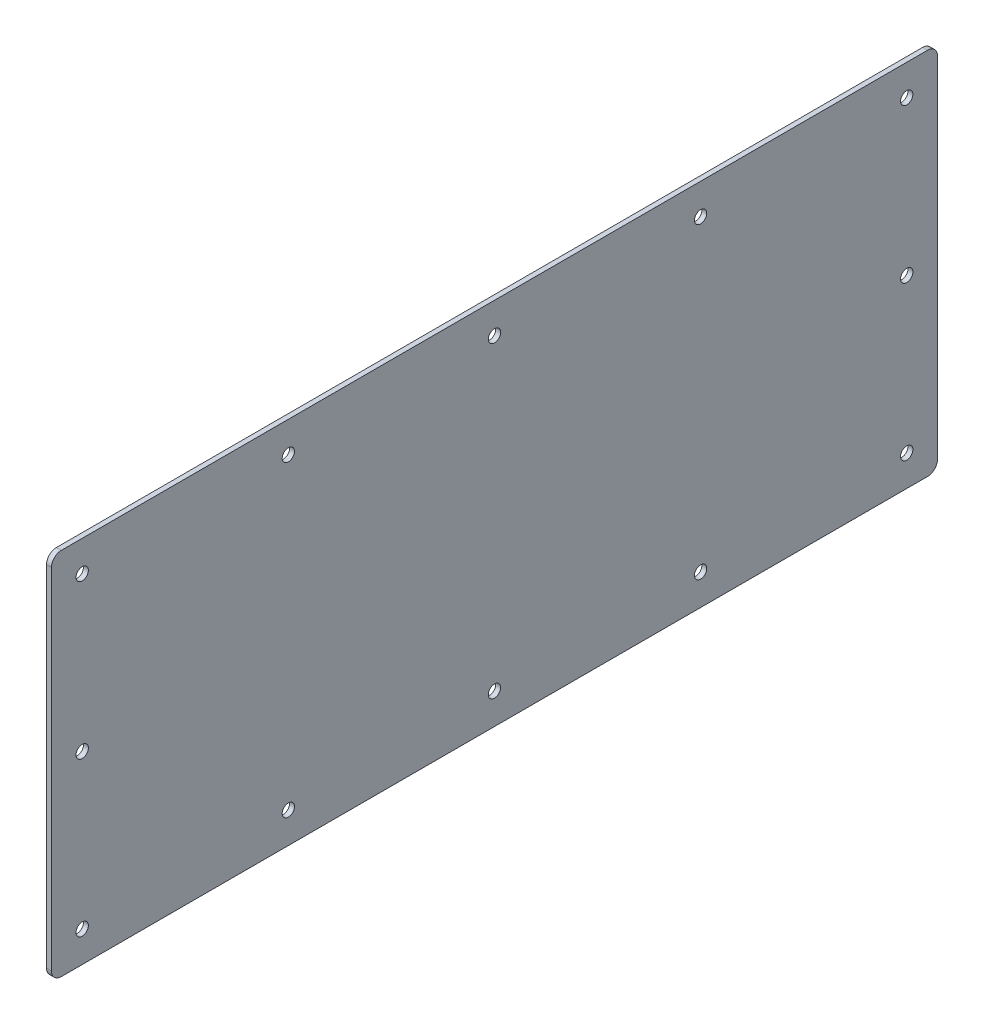
SolidWorks part; units mm, degrees
ref_plane "Front Plane" through (0, 0, 0) normal (1, 0, 0) x (0, 1, 0)
ref_plane "Top Plane" through (0, 0, 0) normal (0, 0, 1) x (0, 1, 0)
ref_plane "Right Plane" through (0, 0, 0) normal (0, 1, 0) x (-1, 0, 0)
sketch "Sketch1" plane through (0, 0, 0) normal (1, 0, 0) x (0, 1, 0)
  line L1 (-95.25, -228.6) -> (95.25, -228.6)
  line L2 (-95.25, -228.6) -> (-95.25, 228.6)
  line L3 (-95.25, 228.6) -> (95.25, 228.6)
  line L4 (95.25, -228.6) -> (95.25, 228.6)
  line L5 (-95.25, -228.6) -> (95.25, 228.6) construction
  line L6 (-95.25, 228.6) -> (95.25, -228.6) construction
  point P0 (0, 0)
  dimension "D1" = 190.5
  dimension "D2" = 457.2
extrude "Boss-Extrude1" add sketch "Sketch1" along normal blind 2.54
fillet "Fillet1" radius 5.08 4 edges at (1.27, 95.25, -228.6) (1.27, -95.25, -228.6) (1.27, -95.25, 228.6) (1.27, 95.25, 228.6)
sketch "Sketch2" plane through (0, 0, 0) normal (-1, 0, 0) x (0, 0, 1)
  circle A1 centre (-257.175, 0) radius 3.175
  circle A2 centre (-257.175, 0) radius 3.175
  circle A3 centre (-106.3625, -79.375) radius 3.175
  circle A4 centre (-106.3625, -79.375) radius 3.175
  circle A5 centre (0, -79.375) radius 3.175
  circle A6 centre (0, -79.375) radius 3.175
  circle A7 centre (106.3625, -79.375) radius 3.175
  circle A8 centre (106.3625, -79.375) radius 3.175
  circle A9 centre (212.725, -79.375) radius 3.175
  circle A10 centre (212.725, -79.375) radius 3.175
  circle A11 centre (212.725, 79.375) radius 3.175
  circle A12 centre (212.725, 79.375) radius 3.175
  circle A13 centre (212.725, 0) radius 3.175
  circle A14 centre (212.725, 0) radius 3.175
  circle A15 centre (-257.175, -79.375) radius 3.175
  circle A16 centre (-257.175, -79.375) radius 3.175
  circle A17 centre (-363.5375, -79.375) radius 3.175
  circle A18 centre (-363.5375, -79.375) radius 3.175
  circle A19 centre (-257.175, 79.375) radius 3.175
  circle A20 centre (-257.175, 79.375) radius 3.175
  circle A21 centre (-106.3625, 79.375) radius 3.175
  circle A22 centre (-106.3625, 79.375) radius 3.175
  circle A23 centre (-212.725, 79.375) radius 3.175
  circle A24 centre (-212.725, 79.375) radius 3.175
  circle A25 centre (-212.725, 0) radius 3.175
  circle A26 centre (-212.725, 0) radius 3.175
  circle A27 centre (-212.725, -79.375) radius 3.175
  circle A28 centre (-212.725, -79.375) radius 3.175
  circle A29 centre (-576.2625, -79.375) radius 3.175
  circle A30 centre (-576.2625, -79.375) radius 3.175
  circle A31 centre (-469.9, -79.375) radius 3.175
  circle A32 centre (-469.9, -79.375) radius 3.175
  circle A33 centre (106.3625, 79.375) radius 3.175
  circle A34 centre (106.3625, 79.375) radius 3.175
  circle A35 centre (0, 79.375) radius 3.175
  circle A36 centre (0, 79.375) radius 3.175
  circle A37 centre (-682.625, 79.375) radius 3.175
  circle A38 centre (-682.625, 79.375) radius 3.175
  circle A39 centre (-576.2625, 79.375) radius 3.175
  circle A40 centre (-576.2625, 79.375) radius 3.175
  circle A41 centre (-682.625, -79.375) radius 3.175
  circle A42 centre (-682.625, -79.375) radius 3.175
  circle A43 centre (-469.9, 79.375) radius 3.175
  circle A44 centre (-469.9, 79.375) radius 3.175
  circle A45 centre (-682.625, 0) radius 3.175
  circle A46 centre (-682.625, 0) radius 3.175
  circle A47 centre (-363.5375, 79.375) radius 3.175
  circle A48 centre (-363.5375, 79.375) radius 3.175
  circle A49 centre (-831.85, -79.375) radius 3.175
  circle A50 centre (-831.85, -79.375) radius 3.175
  circle A51 centre (-831.85, 79.375) radius 3.175
  circle A52 centre (-831.85, 79.375) radius 3.175
  circle A53 centre (-727.075, 79.375) radius 3.175
  circle A54 centre (-727.075, 79.375) radius 3.175
  circle A55 centre (-727.075, -79.375) radius 3.175
  circle A56 centre (-727.075, -79.375) radius 3.175
  circle A57 centre (-936.625, 0) radius 3.175
  circle A58 centre (-936.625, 0) radius 3.175
  circle A59 centre (-727.075, 0) radius 3.175
  circle A60 centre (-727.075, 0) radius 3.175
  circle A61 centre (-936.625, 79.375) radius 3.175
  circle A62 centre (-936.625, 79.375) radius 3.175
  circle A63 centre (-936.625, -79.375) radius 3.175
  circle A64 centre (-936.625, -79.375) radius 3.175
  dimension "D1" = 0
  dimension "D2" = 0
  dimension "D3" = 0
  dimension "D4" = 0
  dimension "D5" = 0
  dimension "D6" = 0
  dimension "D7" = 0
  dimension "D8" = 0
  dimension "D9" = 0
  dimension "D10" = 0
  dimension "D11" = 0
  dimension "D12" = 0
  dimension "D13" = 0
  dimension "D14" = 0
  dimension "D15" = 0
  dimension "D16" = 0
  dimension "D17" = 0
  dimension "D18" = 0
  dimension "D19" = 0
  dimension "D20" = 0
  dimension "D21" = 0
  dimension "D22" = 0
  dimension "D23" = 0
  dimension "D24" = 0
  dimension "D25" = 0
  dimension "D26" = 0
  dimension "D27" = 0
  dimension "D28" = 0
  dimension "D29" = 0
  dimension "D30" = 0
  dimension "D31" = 0
  dimension "D32" = 0
extrude "Cut-Extrude1" cut sketch "Sketch2" against normal through all both and the other way through all
